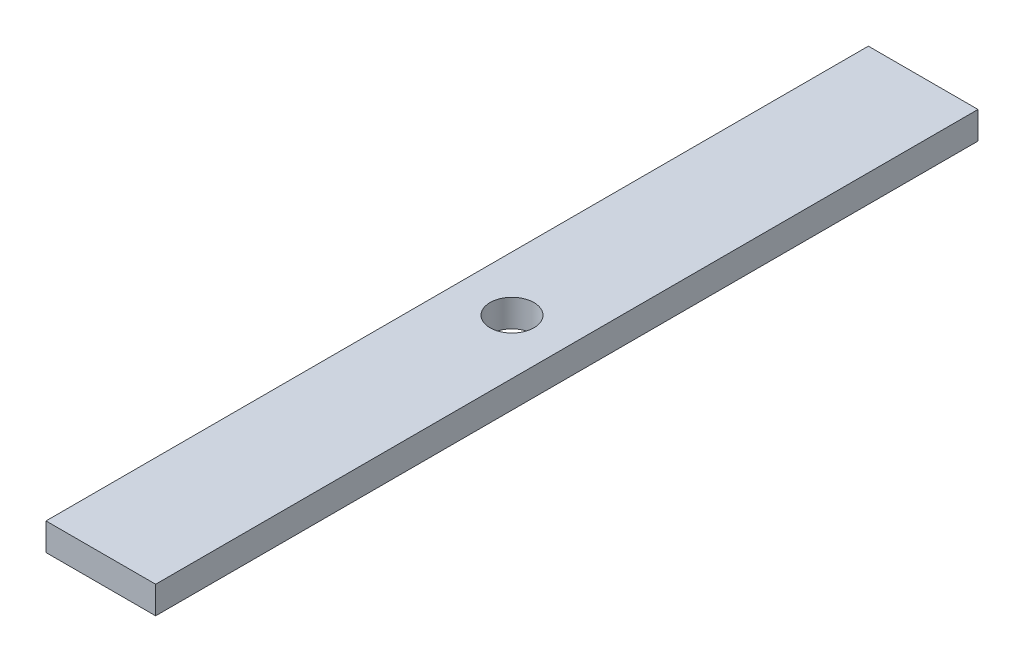
SolidWorks part; units mm, degrees
material "AISI 1045 Steel, cold drawn"
ref_plane "Front Plane" through (0, 0, 0) normal (0, 0, 1) x (1, 0, 0)
ref_plane "Top Plane" through (0, 0, 0) normal (0, 1, 0) x (1, 0, 0)
ref_plane "Right Plane" through (0, 0, 0) normal (1, 0, 0) x (0, 0, -1)
sketch "Sketch1" plane through (0, 0, 0) normal (0, 0, 1) x (1, 0, 0)
  line L1 (-10, 2.5) -> (10, 2.5)
  line L2 (-10, 2.5) -> (-10, -2.5)
  line L3 (-10, -2.5) -> (10, -2.5)
  line L4 (10, 2.5) -> (10, -2.5)
  point P4 (10, 0)
  point P6 (0, 2.5)
  dimension "D1" = 20
  dimension "D2" = 5
extrude "Boss-Extrude1" add sketch "Sketch1" along normal mid plane 212
sketch "Sketch2" plane through (0, 2.5, 0) normal (0, 1, 0) x (1, 0, 0)
  line L0 (0, 0) -> (35.2363, 0) construction
  circle A0 centre (0, 87.5) radius 4
  circle A1 centre (0, 0) radius 4
  circle A2 centre (0, -87.5) radius 4
  dimension "D1" = 8
  dimension "D2" = 175
extrude "Holes for 20mm strip ONLY" cut sketch "Sketch2" against normal through all
sketch "Sketch3" plane through (0, 2.5, 0) normal (0, 1, 0) x (1, 0, 0)
  line L0 (0, 0) -> (65.8821, 0) construction
  line L1 (10, -106) -> (-10, -106) construction
  circle A0 centre (0, -50) radius 2.5
  circle A1 centre (0, -150) radius 2.5
  circle A2 centre (0, 150) radius 2.5
  circle A3 centre (0, 50) radius 2.5
  point P7 (0, -106)
  dimension "D2" = 5
  dimension "D1" = 100
  dimension "D3" = 300
extrude "Cut-Extrude1" [suppressed] cut sketch "Sketch3" against normal through all
sketch "Sketch4" [suppressed] plane through (0, 2.5, 0) normal (0, 1, 0) x (1, 0, 0)
  line L0 (-10, -106) -> (-10, 106) construction
  line L1 (10, -26) -> (-10, -26)
  line L2 (10, -26) -> (10, 26)
  line L3 (10, 26) -> (-10, 26)
  line L4 (-10, -26) -> (-10, 26)
  line L5 (10, -26) -> (-10, 26) construction
  line L6 (10, 26) -> (-10, -26) construction
  point P0 (0, 0)
  dimension "D1" = 52
extrude "Cut-Extrude2" [suppressed] cut sketch "Sketch4" against normal through all flip side to cut
sketch "Sketch5" plane through (0, 2.5, 0) normal (0, 1, 0) x (1, 0, 0)
  line L1 (-25.7525, -75) -> (25.7525, -75)
  line L2 (-25.7525, -75) -> (-25.7525, 75)
  line L3 (-25.7525, 75) -> (25.7525, 75)
  line L4 (25.7525, -75) -> (25.7525, 75)
  line L5 (-25.7525, -75) -> (25.7525, 75) construction
  line L6 (-25.7525, 75) -> (25.7525, -75) construction
  point P0 (0, 0)
  dimension "D1" = 150
extrude "Cut-Extrude3" cut sketch "Sketch5" against normal through all flip side to cut
